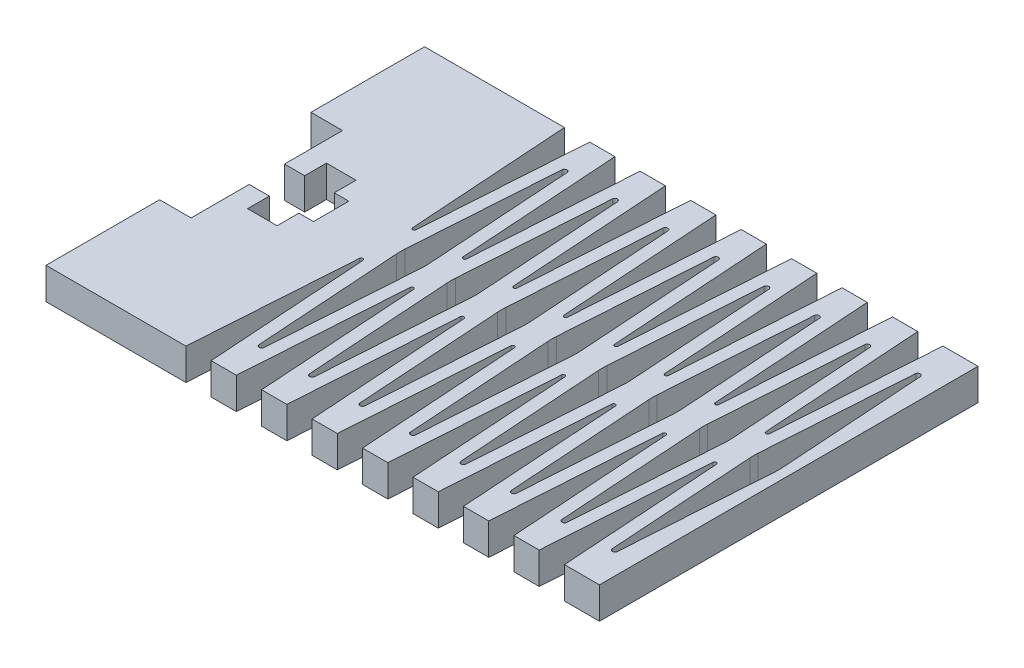
SolidWorks part; units mm, degrees
ref_plane "Front Plane" through (0, 0, 0) normal (0, 0, 1) x (1, 0, 0)
ref_plane "Top Plane" through (0, 0, 0) normal (0, 1, 0) x (1, 0, 0)
ref_plane "Right Plane" through (0, 0, 0) normal (1, 0, 0) x (0, 0, -1)
sketch "Sketch1" plane through (0, 0, 0) normal (0, 1, 0) x (1, 0, 0)
  line L0 (0, 11.43) -> (3.175, 11.43)
  line L1 (0, 0) -> (14.0789, 0)
  line L2 (0, 0) -> (0, 11.43)
  line L3 (0, 38.1) -> (14.0789, 38.1)
  line L4 (52.1789, 0) -> (55.7024, 0)
  line L5 (3.175, 11.43) -> (3.175, 17.272)
  line L6 (3.175, 26.67) -> (0, 26.67)
  line L7 (0, 19.05) -> (67.087, 19.05) construction
  line L8 (3.175, 20.828) -> (5.207, 20.828)
  line L9 (5.207, 23.0188) -> (8.1836, 23.0188)
  line L10 (5.207, 23.0188) -> (5.207, 20.828)
  line L11 (5.207, 15.0813) -> (8.1836, 15.0813)
  line L12 (8.1836, 23.0188) -> (8.1836, 20.828)
  line L13 (9.652, 20.828) -> (9.652, 17.272)
  line L14 (9.652, 17.272) -> (8.1836, 17.272)
  line L15 (3.175, 20.828) -> (3.175, 26.67)
  line L16 (0, 26.67) -> (0, 38.1)
  line L17 (8.1836, 20.828) -> (9.652, 20.828)
  line L18 (5.207, 17.272) -> (3.175, 17.272)
  line L19 (5.207, 17.272) -> (5.207, 15.0813)
  line L20 (8.1836, 17.272) -> (8.1836, 15.0813)
  line L21 (14.0789, 38.1) -> (15.1715, 21.7111)
  line L22 (15.3489, 38.1) -> (15.3489, 0) construction
  line L23 (16.6189, 38.1) -> (15.5263, 21.7111)
  line L24 (21.6989, 38.1) -> (20.6063, 21.7111)
  line L25 (19.1589, 38.1) -> (20.2515, 21.7111)
  line L26 (26.7789, 38.1) -> (25.6863, 21.7111)
  line L27 (24.2389, 38.1) -> (25.3315, 21.7111)
  line L28 (31.8589, 38.1) -> (30.7663, 21.7111)
  line L29 (29.3189, 38.1) -> (30.4115, 21.7111)
  line L30 (36.9389, 38.1) -> (35.8463, 21.7111)
  line L31 (34.3989, 38.1) -> (35.4915, 21.7111)
  line L32 (42.0189, 38.1) -> (40.9263, 21.7111)
  line L33 (39.4789, 38.1) -> (40.5715, 21.7111)
  line L34 (47.0989, 38.1) -> (46.0063, 21.7111)
  line L35 (44.5589, 38.1) -> (45.6515, 21.7111)
  line L36 (52.1789, 38.1) -> (51.0863, 21.7111)
  line L37 (49.6389, 38.1) -> (50.7315, 21.7111)
  line L38 (49.6389, 0) -> (50.7315, 16.3889)
  line L39 (52.1789, 0) -> (51.0863, 16.3889)
  line L40 (44.5589, 0) -> (45.6515, 16.3889)
  line L41 (47.0989, 0) -> (46.0063, 16.3889)
  line L42 (39.4789, 0) -> (40.5715, 16.3889)
  line L43 (42.0189, 0) -> (40.9263, 16.3889)
  line L44 (34.3989, 0) -> (35.4915, 16.3889)
  line L45 (36.9389, 0) -> (35.8463, 16.3889)
  line L46 (29.3189, 0) -> (30.4115, 16.3889)
  line L47 (31.8589, 0) -> (30.7663, 16.3889)
  line L48 (24.2389, 0) -> (25.3315, 16.3889)
  line L49 (26.7789, 0) -> (25.6863, 16.3889)
  line L50 (19.1589, 0) -> (20.2515, 16.3889)
  line L51 (21.6989, 0) -> (20.6063, 16.3889)
  line L52 (16.6189, 0) -> (15.5263, 16.3889)
  line L53 (14.0789, 0) -> (15.1715, 16.3889)
  line L54 (17.8889, 38.1) -> (17.8889, 32.1876) construction
  line L55 (17.7115, 35.4389) -> (16.6471, 19.4724)
  line L56 (18.0663, 35.4389) -> (19.1308, 19.4724)
  line L57 (17.7115, 2.6611) -> (16.6471, 18.6276)
  line L58 (18.0663, 2.6611) -> (19.1308, 18.6276)
  line L59 (22.7915, 35.4389) -> (21.7271, 19.4724)
  line L60 (23.1463, 35.4389) -> (24.2108, 19.4724)
  line L61 (23.1463, 2.6611) -> (24.2108, 18.6276)
  line L62 (22.7915, 2.6611) -> (21.7271, 18.6276)
  line L63 (27.8715, 35.4389) -> (26.8071, 19.4724)
  line L64 (28.2263, 35.4389) -> (29.2908, 19.4724)
  line L65 (28.2263, 2.6611) -> (29.2908, 18.6276)
  line L66 (27.8715, 2.6611) -> (26.8071, 18.6276)
  line L67 (32.9515, 35.4389) -> (31.8871, 19.4724)
  line L68 (33.3063, 35.4389) -> (34.3708, 19.4724)
  line L69 (33.3063, 2.6611) -> (34.3708, 18.6276)
  line L70 (32.9515, 2.6611) -> (31.8871, 18.6276)
  line L71 (38.0315, 35.4389) -> (36.9671, 19.4724)
  line L72 (38.3863, 35.4389) -> (39.4508, 19.4724)
  line L73 (38.3863, 2.6611) -> (39.4508, 18.6276)
  line L74 (38.0315, 2.6611) -> (36.9671, 18.6276)
  line L75 (43.1115, 35.4389) -> (42.0471, 19.4724)
  line L76 (43.4663, 35.4389) -> (44.5308, 19.4724)
  line L77 (43.4663, 2.6611) -> (44.5308, 18.6276)
  line L78 (43.1115, 2.6611) -> (42.0471, 18.6276)
  line L79 (48.1915, 35.4389) -> (47.1271, 19.4724)
  line L80 (48.5463, 35.4389) -> (49.6108, 19.4724)
  line L81 (48.5463, 2.6611) -> (49.6108, 18.6276)
  line L82 (48.1915, 2.6611) -> (47.1271, 18.6276)
  line L83 (53.2715, 35.4389) -> (52.2071, 19.4724)
  line L84 (53.6263, 35.4389) -> (54.6908, 19.4724)
  line L85 (53.6263, 2.6611) -> (54.6908, 18.6276)
  line L86 (53.2715, 2.6611) -> (52.2071, 18.6276)
  line L87 (16.6189, 38.1) -> (19.1589, 38.1)
  line L88 (21.6989, 38.1) -> (24.2389, 38.1)
  line L89 (26.7789, 38.1) -> (29.3189, 38.1)
  line L90 (31.8589, 38.1) -> (34.3989, 38.1)
  line L91 (36.9389, 38.1) -> (39.4789, 38.1)
  line L92 (42.0189, 38.1) -> (44.5589, 38.1)
  line L93 (47.0989, 38.1) -> (49.6389, 38.1)
  line L94 (52.1789, 38.1) -> (55.7024, 38.1)
  line L95 (55.7024, 38.1) -> (55.7024, 0)
  line L96 (47.0989, 0) -> (49.6389, 0)
  line L97 (42.0189, 0) -> (44.5589, 0)
  line L98 (36.9389, 0) -> (39.4789, 0)
  line L99 (31.8589, 0) -> (34.3989, 0)
  line L100 (26.7789, 0) -> (29.3189, 0)
  line L101 (21.6989, 0) -> (24.2389, 0)
  line L102 (16.6189, 0) -> (19.1589, 0)
  arc A0 (15.5263, 21.7111) -> (15.1715, 21.7111) centre (15.3489, 21.7229) cw
  arc A1 (20.6063, 21.7111) -> (20.2515, 21.7111) centre (20.4289, 21.7229) cw
  arc A2 (25.6863, 21.7111) -> (25.3315, 21.7111) centre (25.5089, 21.7229) cw
  arc A3 (30.7663, 21.7111) -> (30.4115, 21.7111) centre (30.5889, 21.7229) cw
  arc A4 (35.8463, 21.7111) -> (35.4915, 21.7111) centre (35.6689, 21.7229) cw
  arc A5 (40.9263, 21.7111) -> (40.5715, 21.7111) centre (40.7489, 21.7229) cw
  arc A6 (46.0063, 21.7111) -> (45.6515, 21.7111) centre (45.8289, 21.7229) cw
  arc A7 (51.0863, 21.7111) -> (50.7315, 21.7111) centre (50.9089, 21.7229) cw
  arc A8 (51.0863, 16.3889) -> (50.7315, 16.3889) centre (50.9089, 16.3771) ccw
  arc A9 (46.0063, 16.3889) -> (45.6515, 16.3889) centre (45.8289, 16.3771) ccw
  arc A10 (40.9263, 16.3889) -> (40.5715, 16.3889) centre (40.7489, 16.3771) ccw
  arc A11 (35.8463, 16.3889) -> (35.4915, 16.3889) centre (35.6689, 16.3771) ccw
  arc A12 (30.7663, 16.3889) -> (30.4115, 16.3889) centre (30.5889, 16.3771) ccw
  arc A13 (25.6863, 16.3889) -> (25.3315, 16.3889) centre (25.5089, 16.3771) ccw
  arc A14 (20.6063, 16.3889) -> (20.2515, 16.3889) centre (20.4289, 16.3771) ccw
  arc A15 (15.5263, 16.3889) -> (15.1715, 16.3889) centre (15.3489, 16.3771) ccw
  arc A16 (18.0663, 35.4389) -> (17.7115, 35.4389) centre (17.8889, 35.4271) ccw
  arc A17 (18.0663, 2.6611) -> (17.7115, 2.6611) centre (17.8889, 2.6729) cw
  arc A18 (16.6471, 18.6276) -> (16.6471, 19.4724) centre (22.983, 19.05) cw
  arc A19 (19.1308, 18.6276) -> (19.1308, 19.4724) centre (12.7948, 19.05) ccw
  arc A20 (23.1463, 35.4389) -> (22.7915, 35.4389) centre (22.9689, 35.4271) ccw
  arc A21 (24.2108, 18.6276) -> (24.2108, 19.4724) centre (17.8748, 19.05) ccw
  arc A22 (21.7271, 18.6276) -> (21.7271, 19.4724) centre (28.063, 19.05) cw
  arc A23 (23.1463, 2.6611) -> (22.7915, 2.6611) centre (22.9689, 2.6729) cw
  arc A24 (28.2263, 35.4389) -> (27.8715, 35.4389) centre (28.0489, 35.4271) ccw
  arc A25 (29.2908, 18.6276) -> (29.2908, 19.4724) centre (22.9548, 19.05) ccw
  arc A26 (26.8071, 18.6276) -> (26.8071, 19.4724) centre (33.143, 19.05) cw
  arc A27 (28.2263, 2.6611) -> (27.8715, 2.6611) centre (28.0489, 2.6729) cw
  arc A28 (33.3063, 35.4389) -> (32.9515, 35.4389) centre (33.1289, 35.4271) ccw
  arc A29 (34.3708, 18.6276) -> (34.3708, 19.4724) centre (28.0348, 19.05) ccw
  arc A30 (31.8871, 18.6276) -> (31.8871, 19.4724) centre (38.223, 19.05) cw
  arc A31 (33.3063, 2.6611) -> (32.9515, 2.6611) centre (33.1289, 2.6729) cw
  arc A32 (38.3863, 35.4389) -> (38.0315, 35.4389) centre (38.2089, 35.4271) ccw
  arc A33 (39.4508, 18.6276) -> (39.4508, 19.4724) centre (33.1148, 19.05) ccw
  arc A34 (36.9671, 18.6276) -> (36.9671, 19.4724) centre (43.303, 19.05) cw
  arc A35 (38.3863, 2.6611) -> (38.0315, 2.6611) centre (38.2089, 2.6729) cw
  arc A36 (43.4663, 35.4389) -> (43.1115, 35.4389) centre (43.2889, 35.4271) ccw
  arc A37 (44.5308, 18.6276) -> (44.5308, 19.4724) centre (38.1948, 19.05) ccw
  arc A38 (42.0471, 18.6276) -> (42.0471, 19.4724) centre (48.383, 19.05) cw
  arc A39 (43.4663, 2.6611) -> (43.1115, 2.6611) centre (43.2889, 2.6729) cw
  arc A40 (48.5463, 35.4389) -> (48.1915, 35.4389) centre (48.3689, 35.4271) ccw
  arc A41 (49.6108, 18.6276) -> (49.6108, 19.4724) centre (43.2748, 19.05) ccw
  arc A42 (47.1271, 18.6276) -> (47.1271, 19.4724) centre (53.463, 19.05) cw
  arc A43 (48.5463, 2.6611) -> (48.1915, 2.6611) centre (48.3689, 2.6729) cw
  arc A44 (53.6263, 35.4389) -> (53.2715, 35.4389) centre (53.4489, 35.4271) ccw
  arc A45 (54.6908, 18.6276) -> (54.6908, 19.4724) centre (48.3548, 19.05) ccw
  arc A46 (52.2071, 18.6276) -> (52.2071, 19.4724) centre (58.543, 19.05) cw
  arc A47 (53.6263, 2.6611) -> (53.2715, 2.6611) centre (53.4489, 2.6729) cw
  point P90 (15.3489, 19.05)
  point P118 (16.6189, 19.05)
  point P121 (19.1589, 19.05)
  dimension "D13" = 0.1778
  dimension "D17" = 0.1778
  dimension "D18" = 6.35
  dimension "D19" = 6.35
  dimension "D1" = 38.1
  dimension "D2" = 7.62
  dimension "D3" = 15.24
  dimension "D4" = 3.175
  dimension "D5" = 2.032
  dimension "D6" = 1.778
  dimension "D7" = 3.556
  dimension "D8" = 9.652
  dimension "D9" = 2.9766
  dimension "D10" = 7.9375
  dimension "D11" = 3.9688
  dimension "D12" = 1.27
  dimension "D16" = 1.27
  dimension "D14" = 8
  dimension "D20" = 8
extrude "Boss-Extrude1" add sketch "Sketch1" along normal blind 3.175 contours L3 L21 A0 L23 L87 L25 A1 L24 L88 L27 A2 L26 L89 L29 A3 L28 L90 L31 A4 L30 L91 L33 A5 L32 L92 L35 A6 L34 L93 L37 A7 L36 L94 L95 L4 L39 A8 L38 L96 L41 A9 L40 L97 L43 A10 L42 L98 L45 A11 L44 L99 L47 A12 L46 L100 L49 A13 L48 L101 L51 A14 L50 L102 L52 A15 L53 L1 L2 L0 L5 L18 L19 L11 L20 L14 L13 L17 L12 L9 L10 L8 L15 L6 L16
sketch "Sketch3" plane through (0, 3.175, 0) normal (0, 1, 0) x (1, 0, 0)
  line L0 (17.8889, 38.1) -> (17.8889, 0) construction
  line L1 (16.6189, 38.1) -> (19.1589, 38.1) construction
  line L2 (16.6189, 0) -> (19.1589, 0) construction
  line L3 (17.6355, 34.2984) -> (16.6471, 19.4724)
  line L4 (16.6471, 18.6276) -> (17.6355, 3.8016)
  line L5 (16.6189, 38.1) -> (15.5263, 21.7111) construction
  line L6 (16.6189, 0) -> (15.5263, 16.3889) construction
  line L7 (19.1308, 18.6276) -> (18.1424, 3.8016)
  line L8 (18.1424, 34.2984) -> (19.1308, 19.4724)
  line L9 (21.7271, 18.6276) -> (22.7155, 3.8016)
  line L10 (24.2108, 18.6276) -> (23.2224, 3.8016)
  line L11 (23.2224, 34.2984) -> (24.2108, 19.4724)
  line L12 (22.7155, 34.2984) -> (21.7271, 19.4724)
  line L13 (26.8071, 18.6276) -> (27.7955, 3.8016)
  line L14 (29.2908, 18.6276) -> (28.3024, 3.8016)
  line L15 (28.3024, 34.2984) -> (29.2908, 19.4724)
  line L16 (27.7955, 34.2984) -> (26.8071, 19.4724)
  line L17 (31.8871, 18.6276) -> (32.8755, 3.8016)
  line L18 (34.3708, 18.6276) -> (33.3824, 3.8016)
  line L19 (33.3824, 34.2984) -> (34.3708, 19.4724)
  line L20 (32.8755, 34.2984) -> (31.8871, 19.4724)
  line L21 (36.9671, 18.6276) -> (37.9555, 3.8016)
  line L22 (39.4508, 18.6276) -> (38.4624, 3.8016)
  line L23 (38.4624, 34.2984) -> (39.4508, 19.4724)
  line L24 (37.9555, 34.2984) -> (36.9671, 19.4724)
  line L25 (42.0471, 18.6276) -> (43.0355, 3.8016)
  line L26 (44.5308, 18.6276) -> (43.5424, 3.8016)
  line L27 (43.5424, 34.2984) -> (44.5308, 19.4724)
  line L28 (43.0355, 34.2984) -> (42.0471, 19.4724)
  line L29 (47.1271, 18.6276) -> (48.1155, 3.8016)
  line L30 (49.6108, 18.6276) -> (48.6224, 3.8016)
  line L31 (48.6224, 34.2984) -> (49.6108, 19.4724)
  line L32 (48.1155, 34.2984) -> (47.1271, 19.4724)
  line L33 (52.2071, 18.6276) -> (53.1955, 3.8016)
  line L34 (54.6908, 18.6276) -> (53.7024, 3.8016)
  line L35 (53.7024, 34.2984) -> (54.6908, 19.4724)
  line L36 (53.1955, 34.2984) -> (52.2071, 19.4724)
  arc A0 (16.6471, 18.6276) -> (16.6471, 19.4724) centre (22.983, 19.05) cw
  arc A1 (19.1308, 18.6276) -> (19.1308, 19.4724) centre (12.7948, 19.05) ccw
  arc A2 (18.1424, 3.8016) -> (17.6355, 3.8016) centre (17.8889, 3.8185) cw
  arc A3 (18.1424, 34.2984) -> (17.6355, 34.2984) centre (17.8889, 34.2815) ccw
  arc A4 (23.2224, 34.2984) -> (22.7155, 34.2984) centre (22.9689, 34.2815) ccw
  arc A5 (23.2224, 3.8016) -> (22.7155, 3.8016) centre (22.9689, 3.8185) cw
  arc A6 (21.7271, 18.6276) -> (21.7271, 19.4724) centre (28.063, 19.05) cw
  arc A7 (24.2108, 18.6276) -> (24.2108, 19.4724) centre (17.8748, 19.05) ccw
  arc A8 (28.3024, 34.2984) -> (27.7955, 34.2984) centre (28.0489, 34.2815) ccw
  arc A9 (28.3024, 3.8016) -> (27.7955, 3.8016) centre (28.0489, 3.8185) cw
  arc A10 (26.8071, 18.6276) -> (26.8071, 19.4724) centre (33.143, 19.05) cw
  arc A11 (29.2908, 18.6276) -> (29.2908, 19.4724) centre (22.9548, 19.05) ccw
  arc A12 (33.3824, 34.2984) -> (32.8755, 34.2984) centre (33.1289, 34.2815) ccw
  arc A13 (33.3824, 3.8016) -> (32.8755, 3.8016) centre (33.1289, 3.8185) cw
  arc A14 (31.8871, 18.6276) -> (31.8871, 19.4724) centre (38.223, 19.05) cw
  arc A15 (34.3708, 18.6276) -> (34.3708, 19.4724) centre (28.0348, 19.05) ccw
  arc A16 (38.4624, 34.2984) -> (37.9555, 34.2984) centre (38.2089, 34.2815) ccw
  arc A17 (38.4624, 3.8016) -> (37.9555, 3.8016) centre (38.2089, 3.8185) cw
  arc A18 (36.9671, 18.6276) -> (36.9671, 19.4724) centre (43.303, 19.05) cw
  arc A19 (39.4508, 18.6276) -> (39.4508, 19.4724) centre (33.1148, 19.05) ccw
  arc A20 (43.5424, 34.2984) -> (43.0355, 34.2984) centre (43.2889, 34.2815) ccw
  arc A21 (43.5424, 3.8016) -> (43.0355, 3.8016) centre (43.2889, 3.8185) cw
  arc A22 (42.0471, 18.6276) -> (42.0471, 19.4724) centre (48.383, 19.05) cw
  arc A23 (44.5308, 18.6276) -> (44.5308, 19.4724) centre (38.1948, 19.05) ccw
  arc A24 (48.6224, 34.2984) -> (48.1155, 34.2984) centre (48.3689, 34.2815) ccw
  arc A25 (48.6224, 3.8016) -> (48.1155, 3.8016) centre (48.3689, 3.8185) cw
  arc A26 (47.1271, 18.6276) -> (47.1271, 19.4724) centre (53.463, 19.05) cw
  arc A27 (49.6108, 18.6276) -> (49.6108, 19.4724) centre (43.2748, 19.05) ccw
  arc A28 (53.7024, 34.2984) -> (53.1955, 34.2984) centre (53.4489, 34.2815) ccw
  arc A29 (53.7024, 3.8016) -> (53.1955, 3.8016) centre (53.4489, 3.8185) cw
  arc A30 (52.2071, 18.6276) -> (52.2071, 19.4724) centre (58.543, 19.05) cw
  arc A31 (54.6908, 18.6276) -> (54.6908, 19.4724) centre (48.3548, 19.05) ccw
  dimension "D1" = 6.35
  dimension "D2" = 0.254
  dimension "D3" = 8
extrude "Cut-Extrude1" cut sketch "Sketch3" against normal through all
